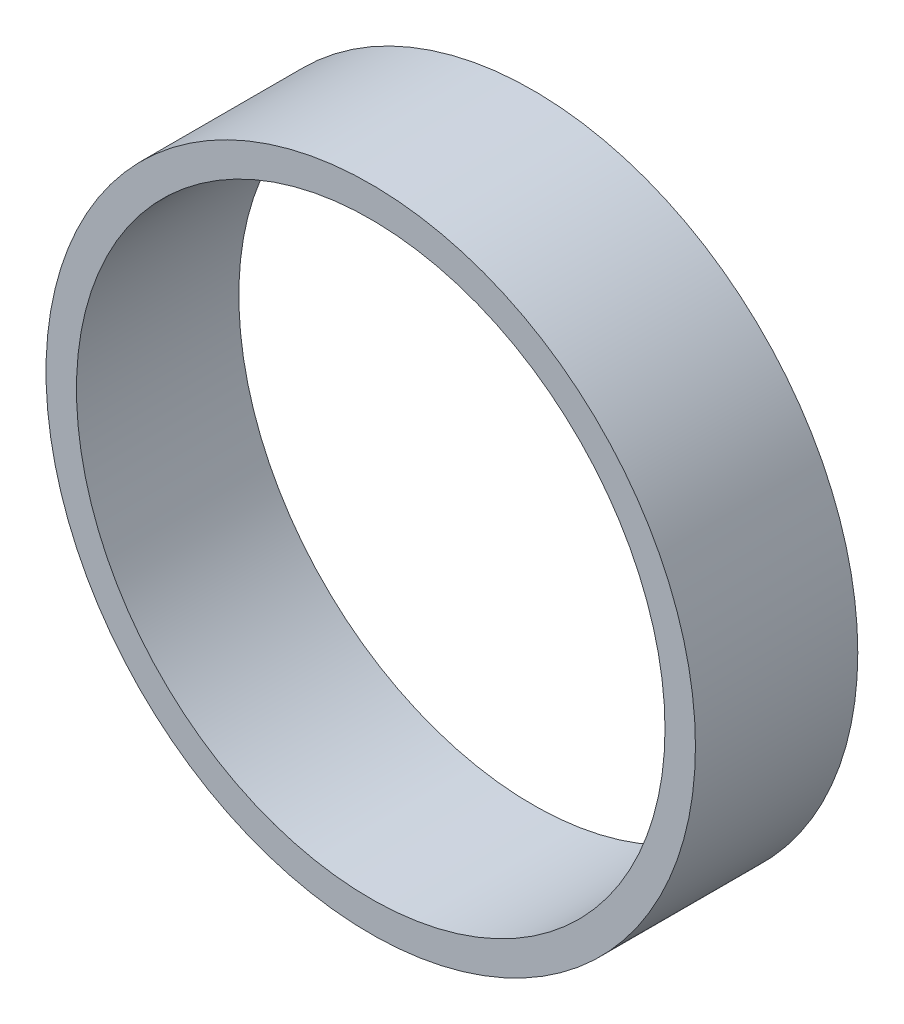
SolidWorks part; units mm, degrees
material "POLYURETHANE (11671)"
ref_plane "Front Plane" through (0, 0, 0) normal (0, 0, 1) x (1, 0, 0)
ref_plane "Top Plane" through (0, 0, 0) normal (0, 1, 0) x (1, 0, 0)
ref_plane "Right Plane" through (0, 0, 0) normal (1, 0, 0) x (0, 0, -1)
sketch "Sketch2" plane through (0, 0, 0) normal (0, 0, 1) x (1, 0, 0)
  circle A0 centre (0, 0) radius 72.5
  circle A1 centre (0, 0) radius 80
  dimension "D1" = 145
  dimension "D2" = 160
extrude "Boss-Extrude1" add sketch "Sketch2" along normal mid plane 40
